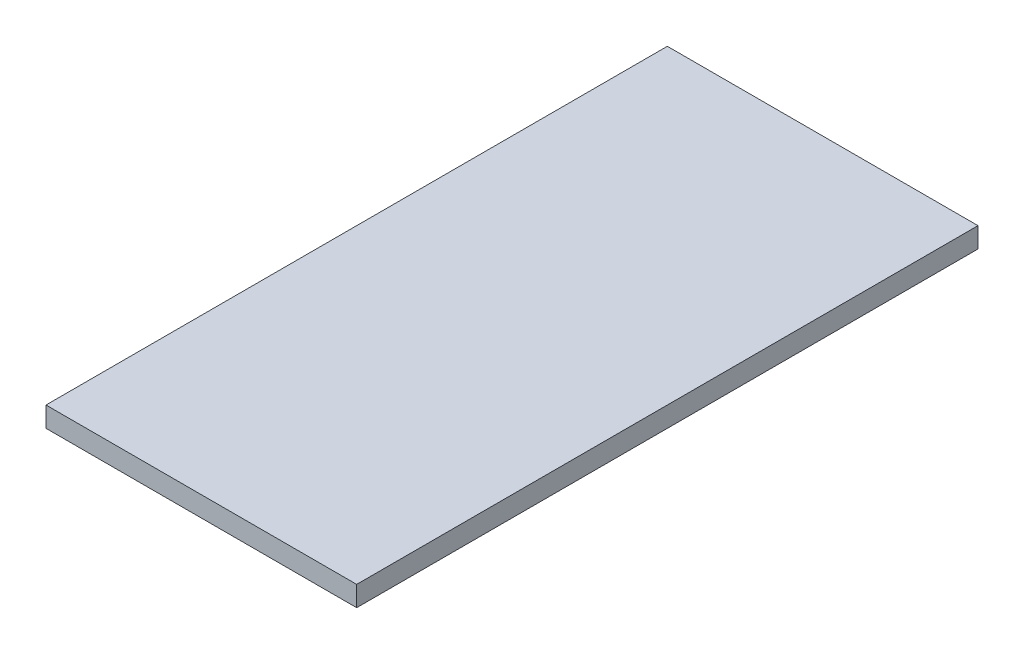
SolidWorks part; units mm, degrees
ref_plane "Front Plane" through (0, 0, 0) normal (0, 0, 1) x (1, 0, 0)
ref_plane "Top Plane" through (0, 0, 0) normal (0, 1, 0) x (1, 0, 0)
ref_plane "Right Plane" through (0, 0, 0) normal (1, 0, 0) x (0, 0, -1)
sketch "Sketch1" plane through (0, 0, 0) normal (0, 1, 0) x (1, 0, 0)
  line L1 (0, 0) -> (304.8, 0)
  line L2 (0, 0) -> (0, 609.6)
  line L3 (0, 609.6) -> (304.8, 609.6)
  line L4 (304.8, 0) -> (304.8, 609.6)
  dimension "D1" = 304.8
  dimension "D2" = 609.6
extrude "Boss-Extrude1" add sketch "Sketch1" along normal blind 19.8438
equation "\"2f\"=16.5455"
